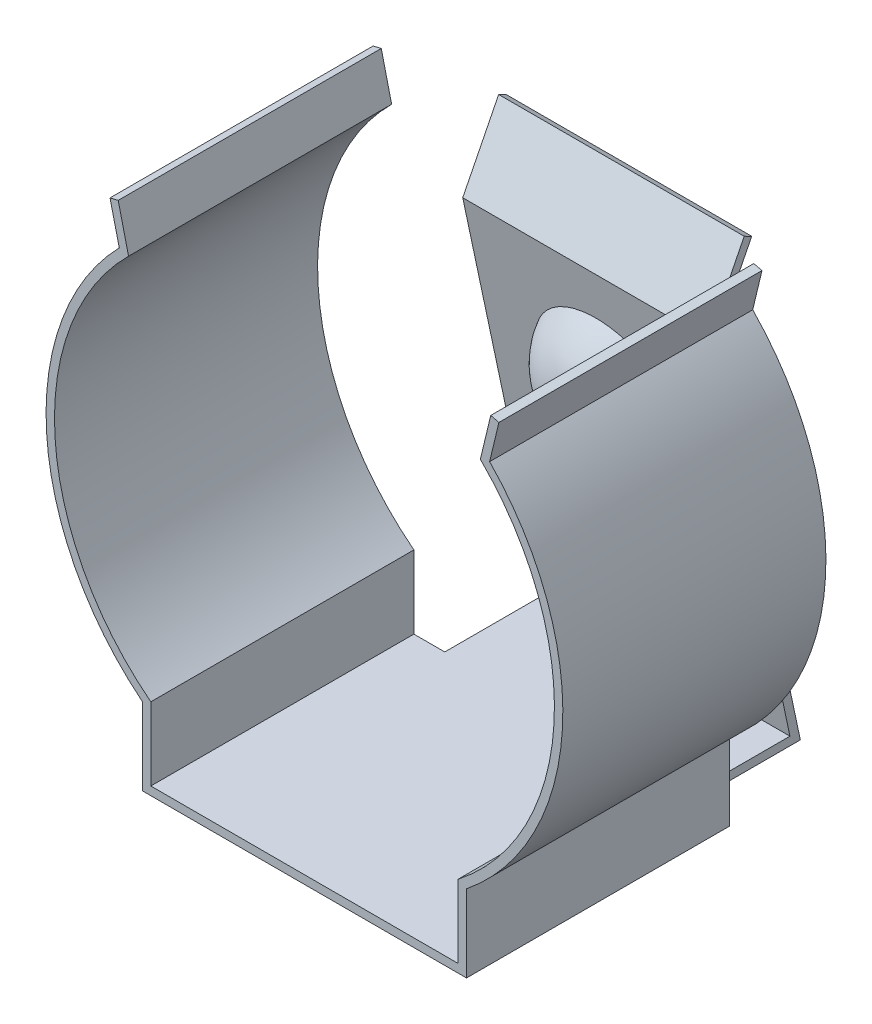
SolidWorks part; units mm, degrees
material "201 Annealed Stainless Steel (SS)"
ref_plane "Front Plane" through (0, 0, 0) normal (0, 0, 1) x (1, 0, 0)
ref_plane "Top Plane" through (0, 0, 0) normal (0, 1, 0) x (1, 0, 0)
ref_plane "Right Plane" through (0, 0, 0) normal (1, 0, 0) x (0, 0, -1)
sketch "Sketch1" plane through (0, 0, 0) normal (0, 0, 1) x (1, 0, 0)
  line L0 (5.5626, 0) -> (-5.5626, 0)
  line L1 (-5.5626, 2.6404) -> (-5.5626, 0)
  line L2 (-6.3686, 16.2089) -> (-6.7437, 17.7724)
  line L3 (-9.05, 4.6345) -> (-9.05, 16.256) construction
  line L4 (0, 0) -> (0, 6.3896) construction
  line L5 (9.05, 4.6345) -> (9.05, 16.256) construction
  line L6 (6.3686, 16.2089) -> (6.7437, 17.7724)
  line L7 (5.5626, 2.6404) -> (5.5626, 0)
  arc A0 (-5.5626, 2.6404) -> (-6.3686, 16.2089) centre (0, 9.779) cw
  arc A1 (5.5626, 2.6404) -> (6.3686, 16.2089) centre (0, 9.779) ccw
  dimension "D3" = 6.7437
  dimension "D6" = 16.256
  dimension "D2" = 18.1
  dimension "D1" = 5.5626
  dimension "D4" = 9.779
extrude "Extrude-Thin1" add sketch "Sketch1" along normal blind 9.525 thin thin type one direction wall 0.3048
sketch "Sketch2" plane through (0, 0, 0) normal (1, 0, 0) x (0, 0, -1)
  line L0 (0, 0) -> (3.6068, 0)
  line L1 (3.6068, 0) -> (0.6505, 13.9165)
  line L2 (0.6505, 13.9165) -> (1.9509, 16.5033)
  line L4 (1.5748, 9.5656) -> (0, 9.5656) construction
  line L5 (0, 2.6404) -> (0, 16.2089) construction
  dimension "D1" = 16.5862
  dimension "D2" = 1.5748
  dimension "D3" = 9.779
  dimension "D4" = 3.6068
extrude "Extrude-Thin2" add sketch "Sketch2" along normal mid plane 8.89 thin
sketch "Sketch3" plane through (0, 0.7331, -3.4511) normal (0, -0.2078, 0.9782) x (1, 0, 0)
  line L0 (4.445, -0.7495) -> (-4.445, -0.7495) construction
  circle A0 centre (0, 9.0295) radius 2.3749
  circle A1 centre (2.897, 3.587) radius 0.7874
  point P4 (0, -0.7495)
  dimension "D1" = 1.5748
  dimension "D2" = 4.7498
  dimension "D3" = 9.779
extrude "Cut-Extrude1" cut sketch "Sketch3" against normal through all
sketch "Sketch4" plane through (0, 0, 0) normal (1, 0, 0) x (0, 0, -1)
  line L0 (1.0813, 11.8886) -> (1.5748, 9.5656) construction
  line L1 (1.0813, 11.8886) -> (2.0683, 7.2425) construction
  line L2 (1.5748, 9.5656) -> (2.0683, 7.2425) construction
  line L11 (0.0344, 9.2383) -> (0.3057, 9.296)
  line L13 (1.0813, 11.8886) -> (1.018, 12.1868)
  arc A0 (1.0813, 11.8886) -> (0.3057, 9.296) centre (2.5634, 10.0329) ccw
  arc A1 (1.018, 12.1868) -> (0.0344, 9.2383) centre (2.5634, 10.0329) ccw
  dimension "D2" = 2.3749
  dimension "D1" = 0.3048
  dimension "D3" = 1.5748
revolve "Revolve2" add sketch "Sketch4" angle 360 about L11
